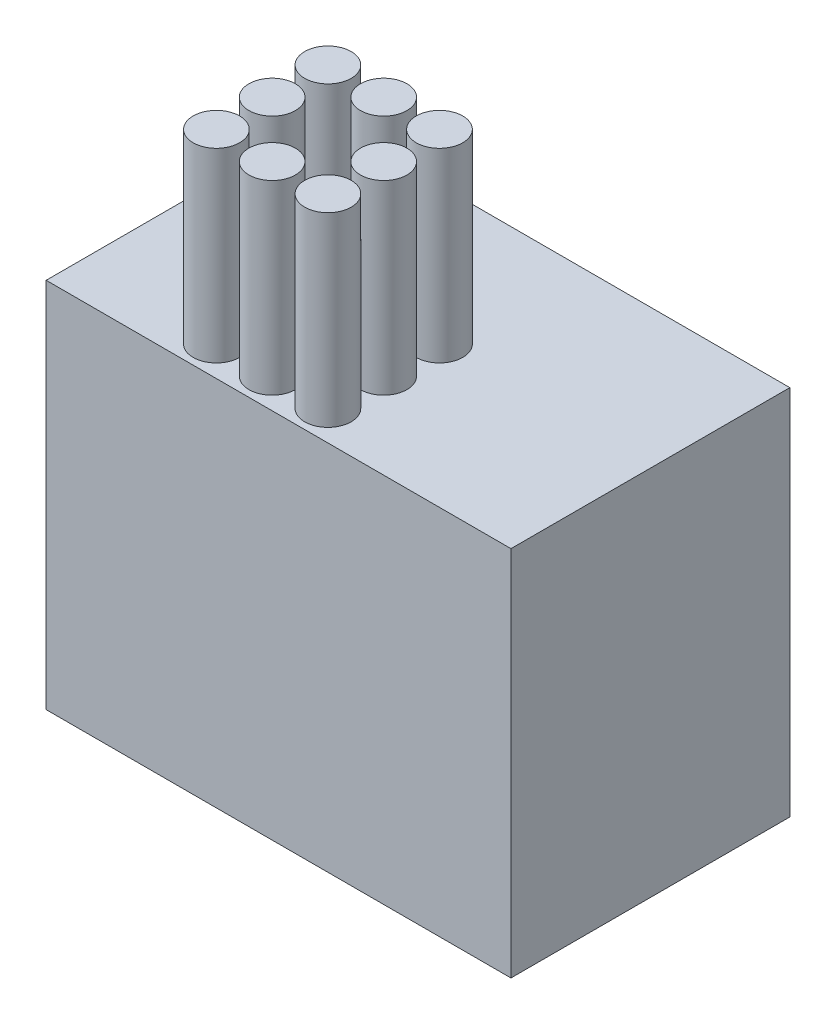
SolidWorks part; units mm, degrees
ref_plane "Front Plane" through (0, 0, 0) normal (0, 0, 1) x (1, 0, 0)
ref_plane "Top Plane" through (0, 0, 0) normal (0, 1, 0) x (1, 0, 0)
ref_plane "Right Plane" through (0, 0, 0) normal (1, 0, 0) x (0, 0, -1)
sketch "Sketch1" plane through (0, 0, 0) normal (0, 0, 1) x (1, 0, 0)
  line L1 (0, 0) -> (127, 0)
  line L2 (0, 0) -> (0, -101.6)
  line L3 (0, -101.6) -> (127, -101.6)
  line L4 (127, 0) -> (127, -101.6)
  dimension "D1" = 127
  dimension "D2" = 101.6
extrude "Boss-Extrude1" add sketch "Sketch1" along normal blind 76.2
sketch "Sketch2" plane through (0, 0, 0) normal (0, 1, 0) x (1, 0, 0)
  circle A0 centre (68.8192, -37.5474) radius 6.35
  dimension "D1" = 12.7
extrude "Boss-Extrude3" add sketch "Sketch2" along normal blind 50.8 contours A0
pattern_linear "LPattern2" count 3 spacing 15.24 along (-1, 0, 0) count 3 spacing 15.24 along (0, 0, 1) skipping (1, 1) of "Boss-Extrude3"
